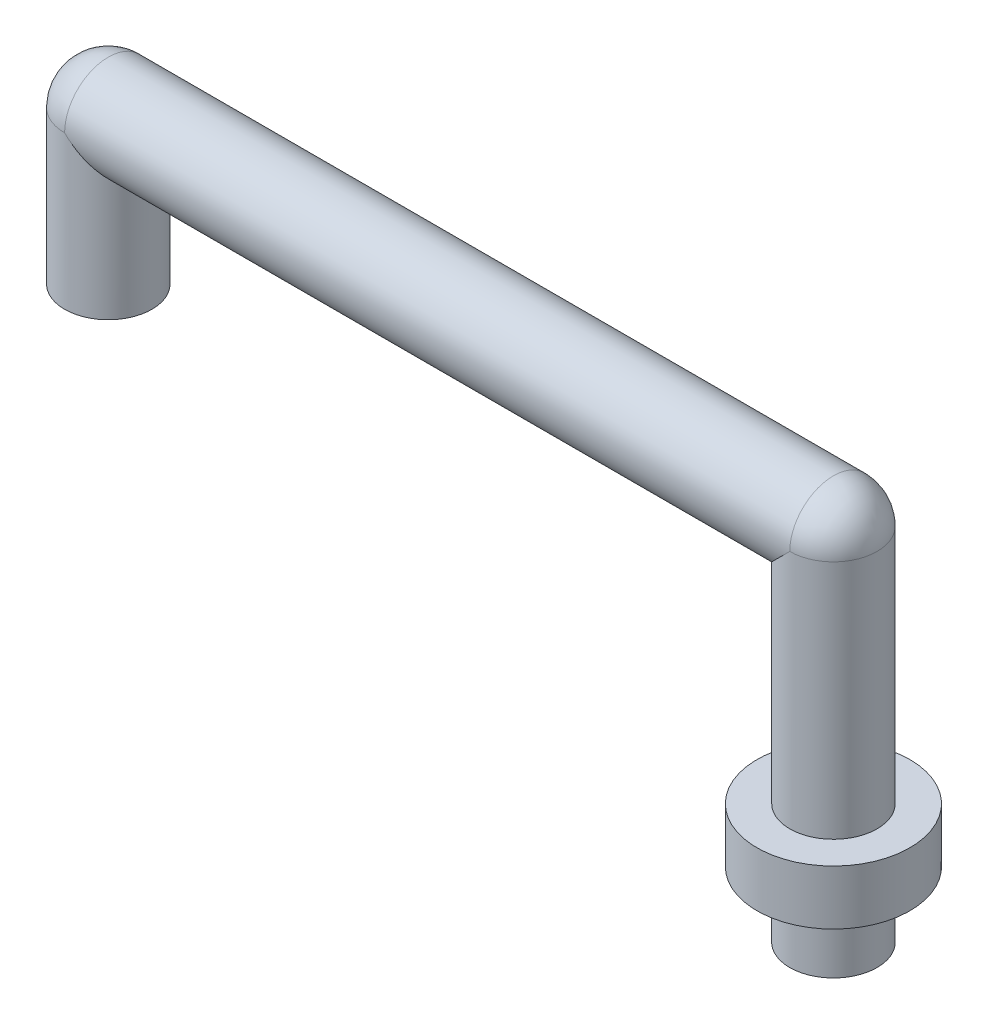
SolidWorks part; units mm, degrees
ref_plane "Front Plane" through (0, 0, 0) normal (0, 0, 1) x (1, 0, 0)
ref_plane "Top Plane" through (0, 0, 0) normal (0, 1, 0) x (1, 0, 0)
ref_plane "Right Plane" through (0, 0, 0) normal (1, 0, 0) x (0, 0, -1)
sketch "Sketch2" plane through (0, 0, 0) normal (0, 1, 0) x (-1, 0, 0)
  circle A0 centre (0, 0) radius 5.08
  dimension "D1" = 10.16
extrude "Boss-Extrude2" add sketch "Sketch2" along normal blind 41.91
sketch "Sketch3" plane through (0, 0, 0) normal (0, 0, 1) x (1, 0, 0)
  line L1 (0, 0) -> (0, 7.62) construction
  line L4 (0, 7.62) -> (0, 13.97)
  line L7 (0, 7.62) -> (-8.89, 7.62)
  line L8 (-8.89, 7.62) -> (-8.89, 13.97)
  line L9 (-8.89, 13.97) -> (0, 13.97)
  dimension "D1" = 6.35
  dimension "D2" = 8.89
  dimension "D3" = 7.62
revolve "Revolve1" add sketch "Sketch3" angle 360 about L1
sketch "Sketch4" plane through (0, 41.91, 0) normal (0, 1, 0) x (1, 0, 0)
  line L0 (0, 5.08) -> (0, -5.08) construction
  line L1 (-5.08, 0) -> (5.08, 0) construction
  line L2 (0, 5.08) -> (-84.328, 5.08)
  line L3 (-84.328, 5.08) -> (-84.328, 0)
  line L4 (-84.328, 0) -> (5.08, 0)
  arc A2 (5.08, 0) -> (0, 5.08) centre (0, 0) ccw
  dimension "D1" = 10.16
  dimension "D2" = 84.328
revolve "Revolve2" add sketch "Sketch4" angle 360 about L4
sketch "Sketch5" plane through (-84.328, 0, 0) normal (-1, 0, 0) x (0, 0, 1)
  line L0 (0, 46.99) -> (0, 24.13)
  line L1 (-5.08, 41.91) -> (5.08, 41.91) construction
  line L2 (-5.08, 41.91) -> (-5.08, 24.13)
  line L3 (-5.08, 24.13) -> (0, 24.13)
  arc A0 (0, 46.99) -> (-5.08, 41.91) centre (0, 41.91) ccw
  circle A1 centre (0, 41.91) radius 5.08 construction
  dimension "D1" = 22.86
revolve "Revolve3" add sketch "Sketch5" angle 360 about L0
